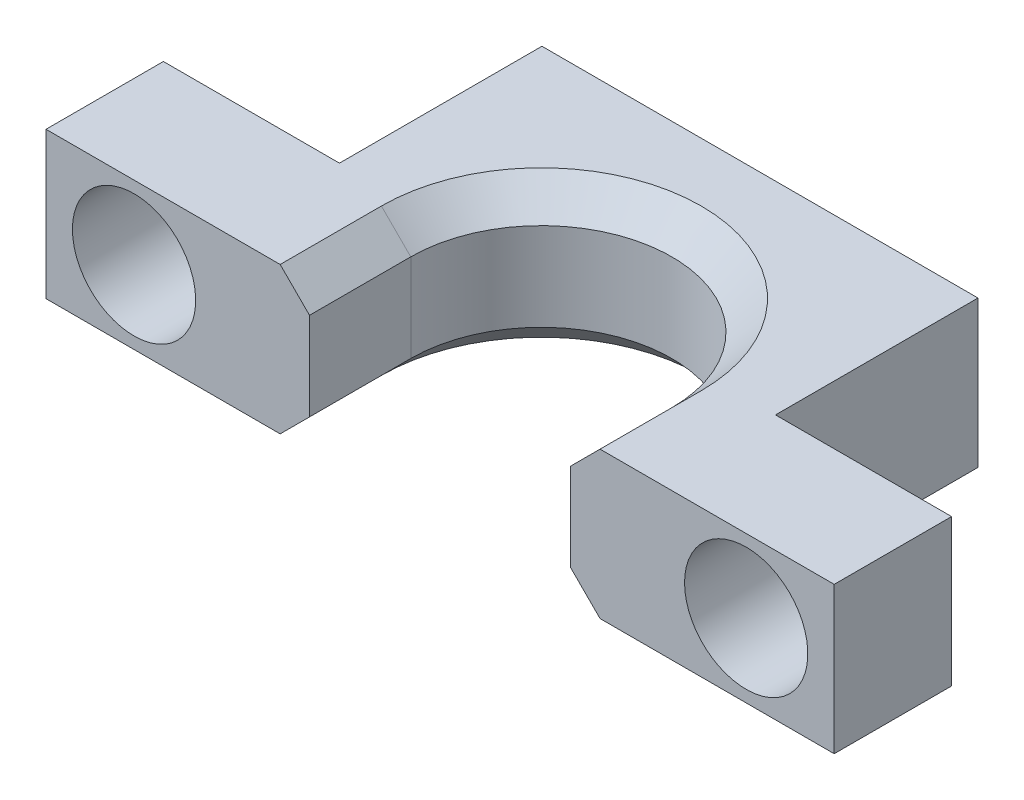
SolidWorks part; units mm, degrees
ref_plane "Front Plane" through (0, 0, 0) normal (0, 0, 1) x (1, 0, 0)
ref_plane "Top Plane" through (0, 0, 0) normal (0, 1, 0) x (1, 0, 0)
ref_plane "Right Plane" through (0, 0, 0) normal (1, 0, 0) x (0, 0, -1)
sketch "Sketch1" plane through (0, 0, 0) normal (0, 1, 0) x (1, 0, 0)
  line L1 (0, 0) -> (72.154, 0)
  line L2 (0, 0) -> (0, 39.439)
  line L3 (0, 39.439) -> (72.154, 39.439)
  line L4 (72.154, 0) -> (72.154, 39.439)
  dimension "D1" = 72.154
extrude "Boss-Extrude1" add sketch "Sketch1" along normal blind 2.5 contours L2 L3 L4 L1
sketch "Sketch2" plane through (0, 2.5, 0) normal (0, 1, 0) x (1, 0, 0)
  line L0 (33.852, 19.4606) -> (18.852, 19.4606)
  line L1 (29.3622, 19.7356) -> (29.3622, 17.7356)
  line L2 (42.7918, 19.7356) -> (42.7918, 17.7356)
  line L3 (38.302, 19.4606) -> (53.302, 19.4606)
  line L4 (53.302, 17.7356) -> (53.302, 19.4606)
  line L5 (33.852, 19.4606) -> (32.352, 19.4606)
  line L6 (36.077, 17.7356) -> (36.077, 19.4606)
  line L7 (39.7918, 19.7356) -> (39.7918, 22.2019)
  line L8 (36.077, 23.1856) -> (39.7918, 23.1856)
  line L9 (33.852, 19.4606) -> (33.852, 17.7356)
  line L10 (38.302, 19.4606) -> (38.302, 17.7356)
  line L11 (33.852, 17.7356) -> (18.852, 17.7356)
  line L12 (39.7918, 23.1856) -> (39.7918, 22.2019)
  line L13 (36.077, 23.1856) -> (32.3622, 23.1856)
  line L14 (38.302, 17.7356) -> (53.302, 17.7356)
  line L15 (18.852, 17.7356) -> (18.852, 19.4606)
  line L16 (18.852, 19.4606) -> (18.852, 19.7356)
  line L17 (33.852, 17.7356) -> (38.302, 17.7356)
  line L18 (36.077, 19.4606) -> (34.352, 19.4606)
  line L19 (36.077, 19.4606) -> (37.802, 19.4606)
  line L20 (37.802, 19.4606) -> (38.302, 19.4606)
  line L21 (34.352, 19.4606) -> (33.852, 19.4606)
  line L22 (18.852, 19.7356) -> (32.3622, 19.7356)
  line L23 (53.302, 19.4606) -> (53.302, 19.7356)
  line L24 (53.302, 19.7356) -> (39.7918, 19.7356)
  line L25 (32.3622, 19.7356) -> (32.3622, 23.1856)
  circle A0 centre (36.077, 19.4606) radius 1.725
  arc A1 (33.852, 19.4606) -> (38.302, 19.4606) centre (36.077, 19.4606) cw
  arc A2 (32.352, 19.4606) -> (39.802, 19.4606) centre (36.077, 19.4606) cw
  dimension "D1" = 3.45
  dimension "D2" = 0.5
  dimension "D3" = 0.5
  dimension "D4" = 1.5
  dimension "D5" = 15
  dimension "D6" = 15
  dimension "D7" = 2
  dimension "D8" = 2
  dimension "D9" = 3
  dimension "D10" = 1.725
  dimension "D11" = 3
extrude "Cut-Extrude1" cut sketch "Sketch2" against normal blind 15 and the other way through all
chamfer "Chamfer1" distance 0.5 angle 45 3 edges at (33.852, 0, -18.5981) (36.077, 0, -21.6856) (38.302, 0, -18.5981)
chamfer "Chamfer2" distance 0.5 angle 45 3 edges at (33.852, 2.5, -18.5981) (36.077, 2.5, -21.6856) (38.302, 2.5, -18.5981)
sketch "Sketch4" plane through (0, 0, -19.7356) normal (0, 0, -1) x (-1, 0, 0)
  line L0 (-42.7918, 1.25) -> (-39.7918, 1.25)
  line L1 (-42.7918, 2.5) -> (-42.7918, 0) construction
  line L2 (-39.7918, 2.5) -> (-39.7918, 0) construction
  line L3 (-39.7918, 1.25) -> (-32.3622, 1.25)
  line L4 (-32.3622, 2.5) -> (-32.3622, 0) construction
  line L5 (-32.3622, 1.25) -> (-29.3622, 1.25)
  line L6 (-29.3622, 2.5) -> (-29.3622, 0) construction
  circle A0 centre (-41.2918, 1.25) radius 1.05
  circle A1 centre (-30.8622, 1.25) radius 1.05
  dimension "D1" = 2.1
  dimension "D2" = 2.1
extrude "Cut-Extrude2" cut sketch "Sketch4" against normal blind 10 contours L0 A0 | L0 A0 | L5 A1 | L5 A1
